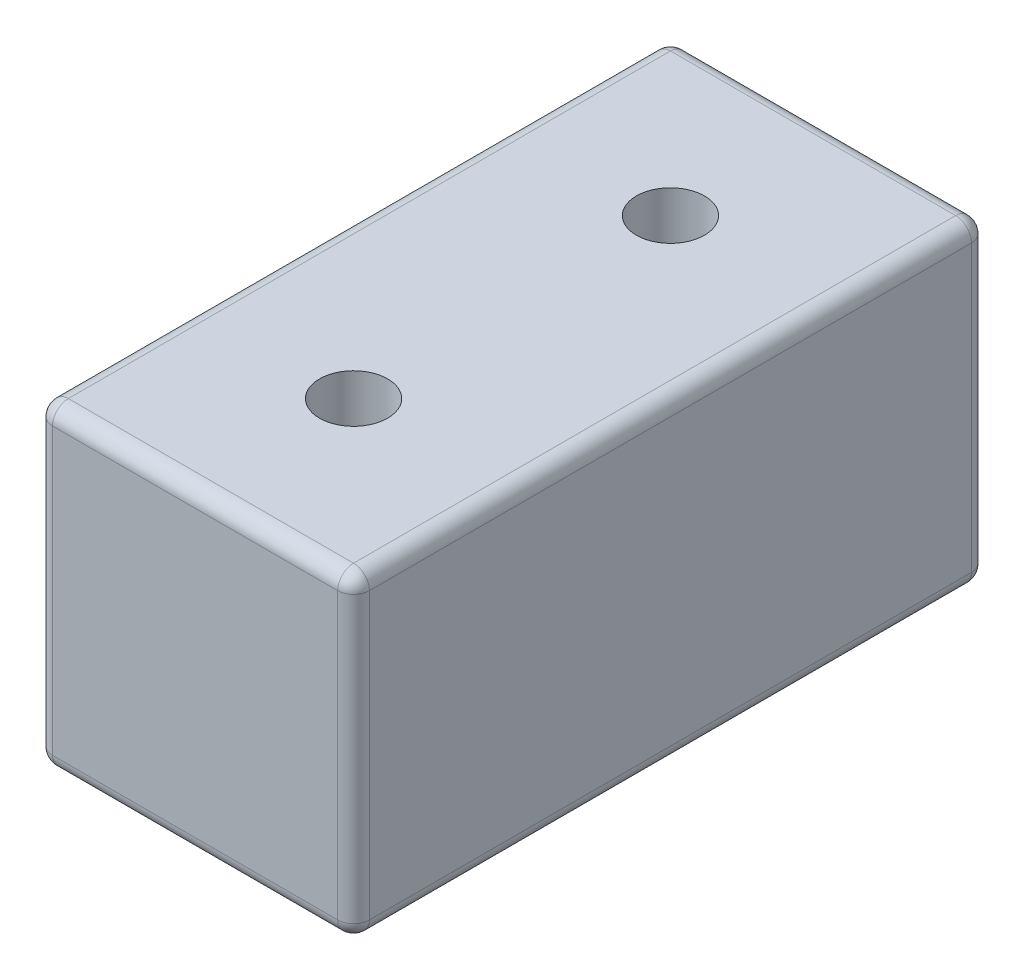
SolidWorks part; units mm, degrees
material "ABS"
ref_plane "前视基准面" through (0, 0, 0) normal (0, 0, 1) x (1, 0, 0)
ref_plane "上视基准面" through (0, 0, 0) normal (0, 1, 0) x (1, 0, 0)
ref_plane "右视基准面" through (0, 0, 0) normal (1, 0, 0) x (0, 0, -1)
other "Configuration Table"
sketch "草图1" plane through (0, 0, 0) normal (0, 0, 1) x (1, 0, 0)
  line L1 (0, 0) -> (20, 0)
  line L2 (0, 0) -> (0, 20)
  line L3 (0, 20) -> (20, 20)
  line L4 (20, 0) -> (20, 20)
  dimension "D1" = 20
  dimension "D2" = 20
extrude "凸台-拉伸1" add sketch "草图1" along normal blind 40
sketch "草图2" plane through (0, 20, 0) normal (0, 1, 0) x (1, 0, 0)
  line L0 (10, 0) -> (10, -40) construction
  line L1 (20, 0) -> (0, 0) construction
  line L2 (20, -40) -> (0, -40) construction
  circle A0 centre (10, -30) radius 2.15
  circle A1 centre (10, -10) radius 2.15
  dimension "D1" = 4.3
  dimension "D2" = 10
  dimension "D3" = 20
extrude "切除-拉伸1" cut sketch "草图2" against normal blind 40
fillet "圆角2" radius 1 12 edges at (0, 10, 0) (10, 0, 0) (20, 10, 0) (10, 20, 0) (0, 10, 40) (10, 0, 40) (20, 10, 40) (0, 20, 20) (20, 20, 20) (20, 0, 20) (0, 0, 20) (10, 20, 40)
